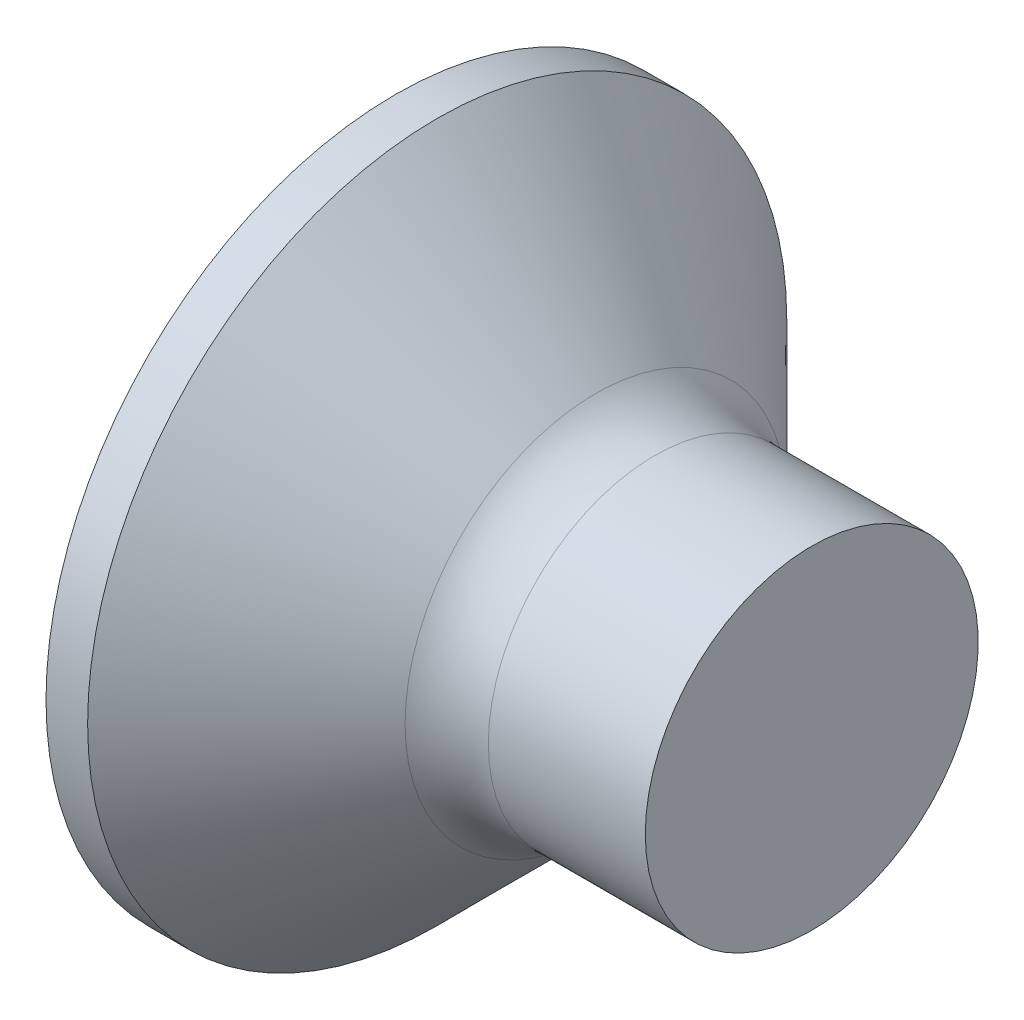
SolidWorks part; units mm, degrees
ref_plane "Plane1" through (0, 0, 0) normal (0, 0, 1) x (1, 0, 0)
ref_plane "Plane2" through (0, 0, 0) normal (0, 1, 0) x (1, 0, 0)
ref_plane "Plane3" through (0, 0, 0) normal (1, 0, 0) x (0, 0, -1)
sketch "BodySke" plane through (0, 0, 0) normal (0, 0, 1) x (1, 0, 0)
  line L0 (0, 0) -> (6, 0)
  line L1 (6, 0) -> (6, 2)
  line L2 (6, 2) -> (3.7, 2)
  line L3 (1.5, -4.2) -> (3.7, -2) construction
  line L4 (-15.875, 0) -> (82.55, 0) construction
  line L5 (1.5, 4.2) -> (3.7, 2)
  line L6 (4.4, 5.175) -> (4.4, -10.7) construction
  line L7 (0, 2.7793) -> (0, -13.0957) construction
  line L8 (1.5, 4.2) -> (1, 4.2)
  arc A0 (0, 0) -> (1, 4.2) centre (9.32, 0) cw
  dimension "Head_ang" = 90
  dimension "Diameter" = 4
  dimension "Advance" = 0.7
  dimension "Thread_nom" = 6
  dimension "Oval_ht" = 1
  dimension "Side_ht" = 2.7
  dimension "Head_dia" = 8.4
  dimension "Length" = 5
revolve "Base-Revolve" add sketch "BodySke" angle 360 about L4
cosmetic thread "ThreadCosmetic" [suppressed] parameters "Thread_length"=1.6, "Thread_minor"=3.22
fillet "Fillet1" radius 1 1 edges at (3.7, 0, 2)
sketch "Sketch3" plane through (0, 0, 0) normal (1, 0, 0) x (0, 0, -1)
  line L0 (0.515, -2.5) -> (-0.515, -2.5)
  line L1 (0.515, -2.5) -> (0.515, 2.5)
  line L2 (-0.515, 2.5) -> (0.515, 2.5)
  line L3 (-0.515, 2.5) -> (-0.515, -2.5)
  dimension "Cross_width" = 1.03
  dimension "D1" = 0.515
  dimension "Cross_dia" = 5
  dimension "D2" = 2.5
ref_plane "Plane4" through (3.1, 0, 0) normal (1, 0, 0) x (0, 0, -1)
sketch "Sketch4" plane through (3.1, 0, 0) normal (1, 0, 0) x (0, 0, -1)
  line L0 (0.515, -0.9544) -> (-0.515, -0.9544)
  line L1 (0.515, -0.9544) -> (0.515, 0.9544)
  line L2 (-0.515, 0.9544) -> (0.515, 0.9544)
  line L3 (-0.515, 0.9544) -> (-0.515, -0.9544)
  dimension "D1" = 1.03
  dimension "D2" = 1.9088
  dimension "D3" = 0.515
  dimension "D4" = 0.9544
loft "Recess" cut profiles "Sketch3", "Sketch4"
pattern_circular "RecPat" count 2 every 90 about axis through (0, 0, 0) along (1, 0, 0) of "Recess"
sketch "RecCorSke" plane through (0, 0, 0) normal (0, 0, 1) x (1, 0, 0)
  line L0 (-3.175, 0) -> (15.875, 0) construction
  line L2 (0, 0) -> (0, 1.0678)
  line L3 (0, 1.0678) -> (3.1, 0.851)
  line L4 (3.1, 0.851) -> (3.3765, 0)
  line L5 (3.3765, 0) -> (0, 0)
  dimension "Diameter" = 1.702
  dimension "Depth" = 3.1
  dimension "Draft_angle" = 4
  dimension "Bottom_angle" = 18
revolve "RecessCore" cut sketch "RecCorSke" angle 360 about L0
sketch "ThdSchSke" plane through (0, 0, 0) normal (0, 0, 1) x (1, 0, 0)
  line L0 (4.4, -1.61) -> (4.1269, -2)
  line L1 (4.4, -1.61) -> (4.6731, -2)
  line L2 (4.6731, -2) -> (4.6731, -2.5)
  line L3 (-3.175, 0) -> (5.1513, 0) construction
  line L5 (4.6731, -2.5) -> (4.1269, -2.5)
  line L6 (4.1269, -2.5) -> (4.1269, -2)
  dimension "Diameter" = 4
  dimension "SideAngle" = 55
  dimension "VeeAngle" = 70
  dimension "Thread_minor" = 3.22
  dimension "Overcut" = 5
  dimension "Start" = 4.4
revolve "ThreadSchematic" [suppressed] cut sketch "ThdSchSke" angle 360 about L3
pattern_linear "ThdSchPat" [suppressed]
sketch "Croquis2" plane through (0, 0, 0) normal (0, 0, 1) x (1, 0, 0)
  line L0 (-8.2658, 0) -> (14.6949, 0) construction
equation "\"D1@Sketch3\" = \"Cross_width@Sketch3\" / 2"
equation "\"D2@Sketch3\" = \"Cross_dia@Sketch3\" / 2"
equation "\"Depth@RecCorSke\" = \"Cross_depth@Plane4\""
equation "\"D1@Sketch4\" = \"Cross_width@Sketch3\""
equation "\"D2@Sketch4\" = \"Cross_dia@Sketch3\" - 2.0 * \"Cross_depth@Plane4\" * tan(26.5  * 0.017453292)"
equation "\"D3@Sketch4\" = \"D1@Sketch4\" / 2"
equation "\"D4@Sketch4\" = \"D2@Sketch4\" / 2"
equation "\"Thread_length@ThreadCosmetic\" = ((sgn( (\"Length@BodySke\" - \"Advance@BodySke\" - \"Side_ht@BodySke\" ) - \"Thread_nom@BodySke\" )-1)*( (\"Length@BodySke\" - \"Advance@BodySke\" - \"Side_ht@BodySke\" ) - \"Thread_nom@BodySke\" ))/-2+ \"Thread_nom@BodySke\""
equation "\"Thread_minor@ThdSchSke\" = \"Thread_minor@ThreadCosmetic\""
equation "\"Diameter@ThdSchSke\" = \"Diameter@BodySke\""
equation "\"Overcut@ThdSchSke\" = \"Diameter@BodySke\" * 1.25"
equation "\"Start@ThdSchSke\" = \"Oval_ht@BodySke\" + \"Length@BodySke\" - \"Thread_length@ThreadCosmetic\"  '---Countersunk---"
equation "\"Num_threads@ThdSchPat\" = int( \"Thread_length@ThreadCosmetic\" / \"Advance@BodySke\" + 0.999 )  + 1"
equation "\"Advance@ThdSchPat\" = \"Thread_length@ThreadCosmetic\" /  (\"Num_threads@ThdSchPat\" - 1) 'relax it"
